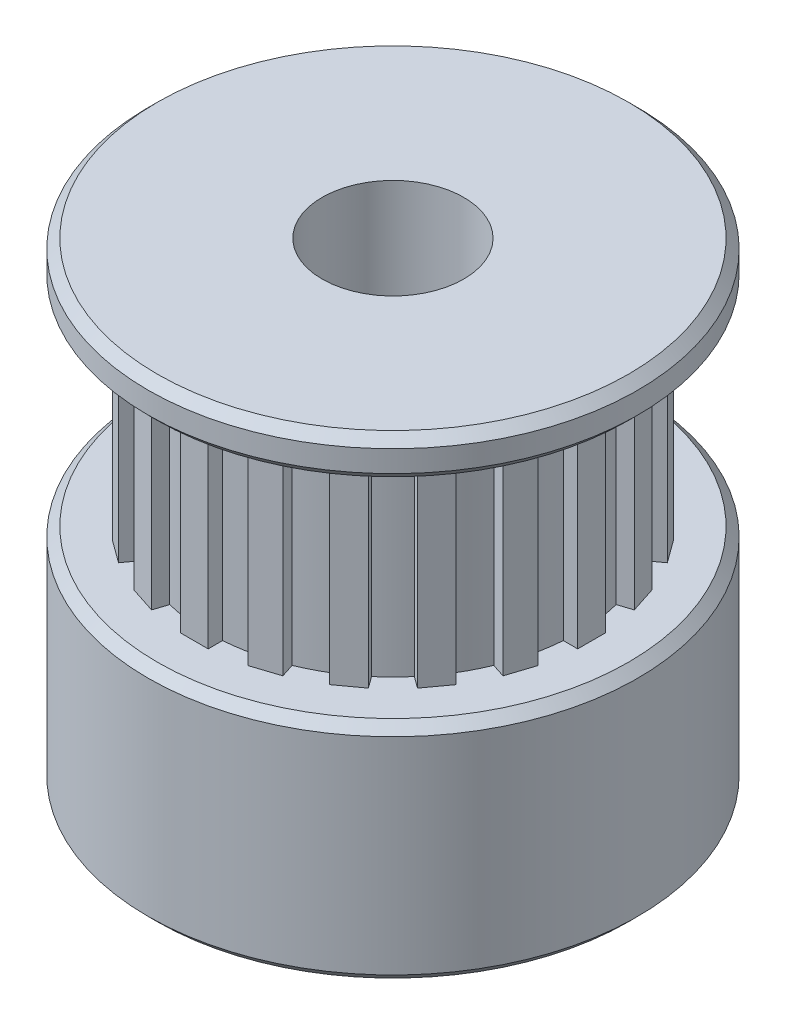
SolidWorks part; units mm, degrees
ref_plane "Front Plane" through (0, 0, 0) normal (0, 0, 1) x (1, 0, 0)
ref_plane "Top Plane" through (0, 0, 0) normal (0, 1, 0) x (1, 0, 0)
ref_plane "Right Plane" through (0, 0, 0) normal (1, 0, 0) x (0, 0, -1)
sketch "Sketch1" plane through (0, 0, 0) normal (0, 1, 0) x (1, 0, 0)
  circle A0 centre (0, 0) radius 7.95
  circle A1 centre (0, 0) radius 2.3
  dimension "D1" = 15.9
  dimension "D2" = 4.6
extrude "Boss-Extrude1" add sketch "Sketch1" along normal blind 7.3
sketch "Sketch2" plane through (0, 7.3, 0) normal (0, 1, 0) x (1, 0, 0)
  line L0 (1.5652, 6.2734) -> (1.4209, 5.8293)
  line L1 (-0.45, 6.45) -> (0.45, 6.45)
  line L2 (-0.45, 6.45) -> (-0.45, 5.9831)
  line L4 (0.45, 6.45) -> (0.45, 5.9831)
  line L7 (1.5652, 6.2734) -> (2.4211, 5.9953)
  line L8 (2.4211, 5.9953) -> (2.2769, 5.5512)
  line L10 (3.4272, 5.4827) -> (3.1527, 5.1049)
  line L11 (3.4272, 5.4827) -> (4.1553, 4.9537)
  line L12 (4.1553, 4.9537) -> (3.8808, 4.5759)
  line L14 (4.9537, 4.1553) -> (4.5759, 3.8808)
  line L15 (4.9537, 4.1553) -> (5.4827, 3.4272)
  line L16 (5.4827, 3.4272) -> (5.1049, 3.1527)
  line L18 (5.9953, 2.4211) -> (5.5512, 2.2769)
  line L19 (5.9953, 2.4211) -> (6.2734, 1.5652)
  line L20 (6.2734, 1.5652) -> (5.8293, 1.4209)
  line L22 (6.45, 0.45) -> (5.9831, 0.45)
  line L23 (6.45, 0.45) -> (6.45, -0.45)
  line L24 (6.45, -0.45) -> (5.9831, -0.45)
  line L26 (6.2734, -1.5652) -> (5.8293, -1.4209)
  line L27 (6.2734, -1.5652) -> (5.9953, -2.4211)
  line L28 (5.9953, -2.4211) -> (5.5512, -2.2769)
  line L30 (5.4827, -3.4272) -> (5.1049, -3.1527)
  line L31 (5.4827, -3.4272) -> (4.9537, -4.1553)
  line L32 (4.9537, -4.1553) -> (4.5759, -3.8808)
  line L34 (4.1553, -4.9537) -> (3.8808, -4.5759)
  line L35 (4.1553, -4.9537) -> (3.4272, -5.4827)
  line L36 (3.4272, -5.4827) -> (3.1527, -5.1049)
  line L38 (2.4211, -5.9953) -> (2.2769, -5.5512)
  line L39 (2.4211, -5.9953) -> (1.5652, -6.2734)
  line L40 (1.5652, -6.2734) -> (1.4209, -5.8293)
  line L42 (0.45, -6.45) -> (0.45, -5.9831)
  line L43 (0.45, -6.45) -> (-0.45, -6.45)
  line L44 (-0.45, -6.45) -> (-0.45, -5.9831)
  line L46 (-1.5652, -6.2734) -> (-1.4209, -5.8293)
  line L47 (-1.5652, -6.2734) -> (-2.4211, -5.9953)
  line L48 (-2.4211, -5.9953) -> (-2.2769, -5.5512)
  line L50 (-3.4272, -5.4827) -> (-3.1527, -5.1049)
  line L51 (-3.4272, -5.4827) -> (-4.1553, -4.9537)
  line L52 (-4.1553, -4.9537) -> (-3.8808, -4.5759)
  line L54 (-4.9537, -4.1553) -> (-4.5759, -3.8808)
  line L55 (-4.9537, -4.1553) -> (-5.4827, -3.4272)
  line L56 (-5.4827, -3.4272) -> (-5.1049, -3.1527)
  line L58 (-5.9953, -2.4211) -> (-5.5512, -2.2769)
  line L59 (-5.9953, -2.4211) -> (-6.2734, -1.5652)
  line L60 (-6.2734, -1.5652) -> (-5.8293, -1.4209)
  line L62 (-6.45, -0.45) -> (-5.9831, -0.45)
  line L63 (-6.45, -0.45) -> (-6.45, 0.45)
  line L64 (-6.45, 0.45) -> (-5.9831, 0.45)
  line L66 (-6.2734, 1.5652) -> (-5.8293, 1.4209)
  line L67 (-6.2734, 1.5652) -> (-5.9953, 2.4211)
  line L68 (-5.9953, 2.4211) -> (-5.5512, 2.2769)
  line L70 (-5.4827, 3.4272) -> (-5.1049, 3.1527)
  line L71 (-5.4827, 3.4272) -> (-4.9537, 4.1553)
  line L72 (-4.9537, 4.1553) -> (-4.5759, 3.8808)
  line L74 (-4.1553, 4.9537) -> (-3.8808, 4.5759)
  line L75 (-4.1553, 4.9537) -> (-3.4272, 5.4827)
  line L76 (-3.4272, 5.4827) -> (-3.1527, 5.1049)
  line L78 (-2.4211, 5.9953) -> (-2.2769, 5.5512)
  line L79 (-2.4211, 5.9953) -> (-1.5652, 6.2734)
  line L80 (-1.5652, 6.2734) -> (-1.4209, 5.8293)
  circle A0 centre (0, 0) radius 2.3 construction
  circle A1 centre (0, 0) radius 2.3
  arc A2 (-5.5512, -2.2769) -> (-5.1049, -3.1527) centre (0, 0) ccw
  arc A3 (-4.5759, -3.8808) -> (-3.8808, -4.5759) centre (0, 0) ccw
  arc A4 (-3.1527, -5.1049) -> (-2.2769, -5.5512) centre (0, 0) ccw
  arc A5 (-1.4209, -5.8293) -> (-0.45, -5.9831) centre (0, 0) ccw
  arc A6 (0.45, -5.9831) -> (1.4209, -5.8293) centre (0, 0) ccw
  arc A7 (2.2769, -5.5512) -> (3.1527, -5.1049) centre (0, 0) ccw
  arc A8 (3.8808, -4.5759) -> (4.5759, -3.8808) centre (0, 0) ccw
  arc A9 (5.1049, -3.1527) -> (5.5512, -2.2769) centre (0, 0) ccw
  arc A10 (5.8293, -1.4209) -> (5.9831, -0.45) centre (0, 0) ccw
  arc A11 (5.9831, 0.45) -> (5.8293, 1.4209) centre (0, 0) ccw
  arc A12 (5.5512, 2.2769) -> (5.1049, 3.1527) centre (0, 0) ccw
  arc A13 (4.5759, 3.8808) -> (3.8808, 4.5759) centre (0, 0) ccw
  arc A14 (3.1527, 5.1049) -> (2.2769, 5.5512) centre (0, 0) ccw
  arc A15 (1.4209, 5.8293) -> (0.45, 5.9831) centre (0, 0) ccw
  arc A16 (0.4532, 5.9829) -> (0.45, 5.9831) centre (0, 0) ccw
  arc A17 (-2.2769, 5.5512) -> (-3.1527, 5.1049) centre (0, 0) ccw
  arc A18 (-3.8808, 4.5759) -> (-4.5759, 3.8808) centre (0, 0) ccw
  arc A19 (-5.1049, 3.1527) -> (-5.5512, 2.2769) centre (0, 0) ccw
  arc A20 (-5.8293, 1.4209) -> (-5.9831, 0.45) centre (0, 0) ccw
  arc A21 (-5.9831, -0.45) -> (-5.8293, -1.4209) centre (0, 0) ccw
  arc A22 (-0.45, 5.9831) -> (-1.4209, 5.8293) centre (0, 0) ccw
  point P4 (0, 6)
  point P88 (0, 0)
  dimension "D1" = 12
  dimension "D2" = 0.9
  dimension "D4" = 20
extrude "Boss-Extrude2" add sketch "Sketch2" along normal blind 6.8 contours L2 A22 L80 L79 L78 A17 L76 L75 L74 A18 L72 L71 L70 A19 L68 L67 L66 A20 L64 L63 L62 A21 L60 L59 L58 A2 L56 L55 L54 A3 L52 L51 L50 A4 L48 L47 L46 A5 L44 L43 L42 A6 L40 L39 L38 A7 L36 L35 L34 A8 L32
sketch "Sketch3" plane through (0, 14.1, 0) normal (0, 1, 0) x (1, 0, 0)
  circle A0 centre (0, 0) radius 7.95 construction
  circle A1 centre (0, 0) radius 7.95
  circle A2 centre (0, 0) radius 2.3 construction
  circle A3 centre (0, 0) radius 2.3
extrude "Boss-Extrude3" add sketch "Sketch3" along normal blind 1.3
chamfer "Chamfer1" distance 0.3 angle 45 4 edges at (0, 0, 7.95) (0, 7.3, 7.95) (0, 14.1, 7.95) (0, 15.4, 7.95)
